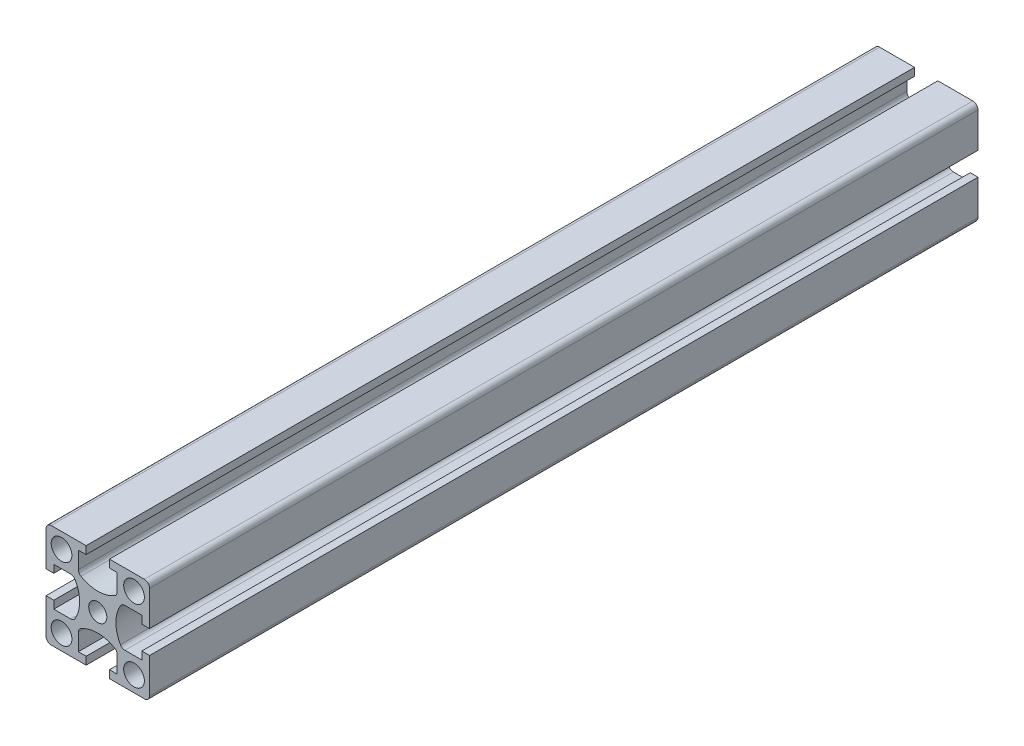
SolidWorks part; units mm, degrees
ref_plane "Front Plane" through (0, 0, 0) normal (0, 0, 1) x (1, 0, 0)
ref_plane "Top Plane" through (0, 0, 0) normal (0, 1, 0) x (1, 0, 0)
ref_plane "Right Plane" through (0, 0, 0) normal (1, 0, 0) x (0, 0, -1)
sketch "Sketch1" plane through (0, 0, 0) normal (0, 0, 1) x (1, 0, 0)
  line L64 (-12.5, 11.25) -> (-12.5, 2.8125)
  line L65 (-12.5, 2.8125) -> (-10.625, 2.8125)
  line L66 (-10.625, 2.8125) -> (-10.625, 4.6875)
  line L67 (-10.625, 4.6875) -> (-6.5461, 4.6875)
  line L68 (-6.5461, -4.6875) -> (-10.625, -4.6875)
  line L69 (-10.625, -4.6875) -> (-10.625, -2.8125)
  line L70 (-10.625, -2.8125) -> (-12.5, -2.8125)
  line L71 (-12.5, -2.8125) -> (-12.5, -11.25)
  line L72 (-11.25, -12.5) -> (-2.8125, -12.5)
  line L73 (-2.8125, -12.5) -> (-2.8125, -10.625)
  line L74 (-2.8125, -10.625) -> (-4.6875, -10.625)
  line L75 (-4.6875, -10.625) -> (-4.6875, -6.5461)
  line L76 (4.6875, -6.5461) -> (4.6875, -10.625)
  line L77 (4.6875, -10.625) -> (2.8125, -10.625)
  line L78 (2.8125, -10.625) -> (2.8125, -12.5)
  line L79 (2.8125, -12.5) -> (11.25, -12.5)
  line L80 (12.5, -11.25) -> (12.5, -2.8125)
  line L81 (12.5, -2.8125) -> (10.625, -2.8125)
  line L82 (10.625, -2.8125) -> (10.625, -4.6875)
  line L83 (10.625, -4.6875) -> (6.5461, -4.6875)
  line L84 (6.5461, 4.6875) -> (10.625, 4.6875)
  line L85 (10.625, 4.6875) -> (10.625, 2.8125)
  line L86 (10.625, 2.8125) -> (12.5, 2.8125)
  line L87 (12.5, 2.8125) -> (12.5, 11.25)
  line L88 (11.25, 12.5) -> (2.8125, 12.5)
  line L89 (2.8125, 12.5) -> (2.8125, 10.625)
  line L90 (2.8125, 10.625) -> (4.6875, 10.625)
  line L91 (4.6875, 10.625) -> (4.6875, 6.5461)
  line L92 (-4.6875, 6.5461) -> (-4.6875, 10.625)
  line L93 (-4.6875, 10.625) -> (-2.8125, 10.625)
  line L94 (-2.8125, 10.625) -> (-2.8125, 12.5)
  line L95 (-2.8125, 12.5) -> (-11.25, 12.5)
  circle A5 centre (-8.75, -8.75) radius 2.5
  circle A6 centre (8.75, -8.75) radius 2.5
  circle A7 centre (8.75, 8.75) radius 2.5
  circle A8 centre (0, 0) radius 2.1875
  circle A9 centre (-8.75, 8.75) radius 2.5
  arc A32 (-11.25, 12.5) -> (-12.5, 11.25) centre (-11.25, 11.25) ccw
  arc A33 (-5.4635, 4.0625) -> (-6.5461, 4.6875) centre (-6.5461, 3.4375) ccw
  arc A34 (-5.4635, -4.0625) -> (-5.4635, 4.0625) centre (-12.5, 0) ccw
  arc A35 (-6.5461, -4.6875) -> (-5.4635, -4.0625) centre (-6.5461, -3.4375) ccw
  arc A36 (-12.5, -11.25) -> (-11.25, -12.5) centre (-11.25, -11.25) ccw
  arc A37 (-4.0625, -5.4635) -> (-4.6875, -6.5461) centre (-3.4375, -6.5461) ccw
  arc A38 (4.0625, -5.4635) -> (-4.0625, -5.4635) centre (0, -12.5) ccw
  arc A39 (4.6875, -6.5461) -> (4.0625, -5.4635) centre (3.4375, -6.5461) ccw
  arc A40 (11.25, -12.5) -> (12.5, -11.25) centre (11.25, -11.25) ccw
  arc A41 (5.4635, -4.0625) -> (6.5461, -4.6875) centre (6.5461, -3.4375) ccw
  arc A42 (5.4635, 4.0625) -> (5.4635, -4.0625) centre (12.5, 0) ccw
  arc A43 (6.5461, 4.6875) -> (5.4635, 4.0625) centre (6.5461, 3.4375) ccw
  arc A44 (12.5, 11.25) -> (11.25, 12.5) centre (11.25, 11.25) ccw
  arc A45 (4.0625, 5.4635) -> (4.6875, 6.5461) centre (3.4375, 6.5461) ccw
  arc A46 (-4.0625, 5.4635) -> (4.0625, 5.4635) centre (0, 12.5) ccw
  arc A47 (-4.6875, 6.5461) -> (-4.0625, 5.4635) centre (-3.4375, 6.5461) ccw
extrude "Boss-Extrude1" add sketch "Sketch1" along normal blind 200
